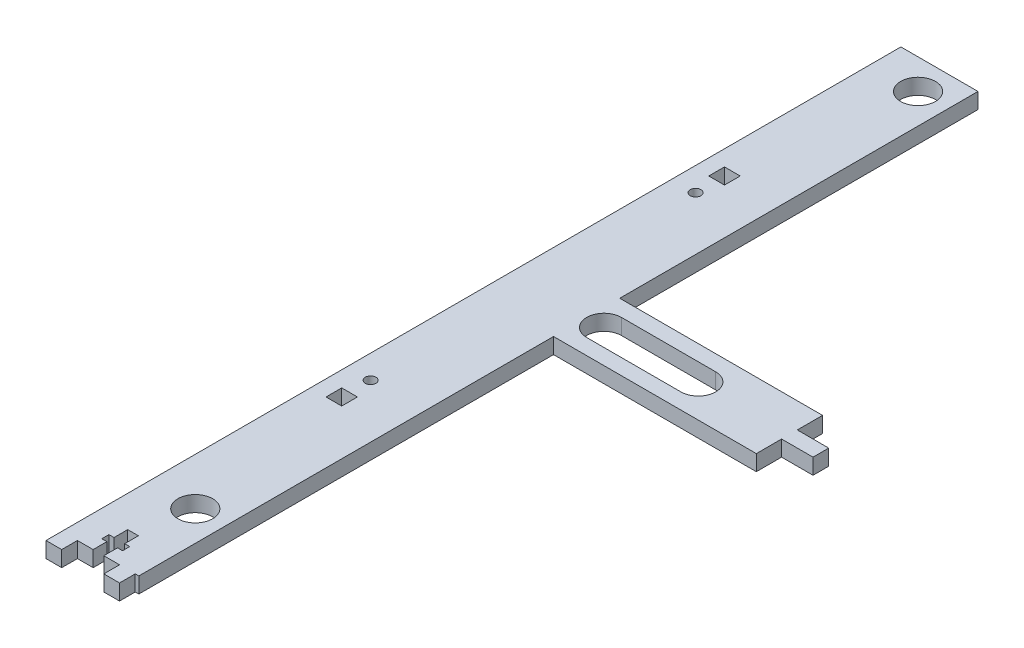
SolidWorks part; units mm, degrees
ref_plane "Front Plane" through (0, 0, 0) normal (0, 0, 1) x (1, 0, 0)
ref_plane "Top Plane" through (0, 0, 0) normal (0, 1, 0) x (1, 0, 0)
ref_plane "Right Plane" through (0, 0, 0) normal (1, 0, 0) x (0, 0, -1)
sketch "Axle Support Plate" plane through (0, 0, 0) normal (0, 1, 0) x (1, 0, 0)
  line L0 (19.05, 146.05) -> (19.05, -146.05) construction
  line L1 (6.35, 158.1601) -> (6.35, -187.325) construction
  line L2 (6.35, -80.518) -> (6.35, -74.168)
  line L3 (6.35, 80.518) -> (12.7, 80.518)
  line L4 (31.1601, -180.975) -> (31.1601, -13.3801)
  line L5 (0, 0) -> (31.1601, 158.1601) construction
  line L6 (0, 0) -> (31.1601, -180.975) construction
  line L8 (0, 158.1601) -> (31.1601, 158.1601)
  line L9 (6.35, -180.975) -> (12.7, -180.975)
  line L10 (6.35, 80.518) -> (6.35, 74.168)
  line L11 (6.35, 74.168) -> (12.7, 74.168)
  line L12 (0, -187.325) -> (0, 158.1601)
  line L13 (12.7, 80.518) -> (12.7, 74.168)
  line L14 (6.35, -80.518) -> (12.7, -80.518)
  line L15 (12.7, -80.518) -> (12.7, -74.168)
  line L16 (6.35, -74.168) -> (12.7, -74.168)
  line L17 (31.1601, 0) -> (0, 0) construction
  line L18 (0, -187.325) -> (6.35, -187.325)
  line L19 (6.35, -187.325) -> (6.35, -180.975)
  line L20 (23.368, -180.975) -> (23.368, -187.325)
  line L21 (23.368, -187.325) -> (29.718, -187.325)
  line L22 (29.718, -187.325) -> (29.718, -180.975)
  line L23 (29.718, -180.975) -> (31.1601, -180.975)
  line L24 (9.525, 80.518) -> (9.525, 65.659) construction
  line L25 (12.7, -180.975) -> (12.7, -175.44)
  line L26 (12.7, -175.44) -> (10.659, -175.44)
  line L27 (10.659, -175.44) -> (10.659, -172.54)
  line L28 (10.659, -172.54) -> (12.7, -172.54)
  line L29 (12.7, -172.54) -> (12.7, -167.005)
  line L30 (12.7, -167.005) -> (17.018, -167.005)
  line L31 (17.018, -167.005) -> (17.018, -172.54)
  line L32 (17.018, -172.54) -> (19.059, -172.54)
  line L33 (19.059, -172.54) -> (19.059, -175.44)
  line L34 (19.059, -175.44) -> (17.018, -175.44)
  line L35 (17.018, -175.44) -> (17.018, -180.975)
  line L36 (17.018, -180.975) -> (23.368, -180.975)
  line L37 (31.1601, 13.3801) -> (113.1203, 13.3801)
  line L38 (113.1203, 13.3801) -> (113.1203, 3.175)
  line L39 (113.1203, -13.3801) -> (31.1601, -13.3801)
  line L40 (38.1903, 0) -> (76.2903, 0) construction
  line L41 (38.1903, 7.0301) -> (76.2903, 7.0301)
  line L42 (38.1903, -7.0301) -> (76.2903, -7.0301)
  line L43 (113.1203, -3.175) -> (125.8203, -3.175)
  line L44 (125.8203, -3.175) -> (125.8203, 3.175)
  line L45 (125.8203, 3.175) -> (113.1203, 3.175)
  line L46 (31.1601, 13.3801) -> (31.1601, 158.1601)
  line L47 (31.1601, 13.3801) -> (31.1601, -13.3801) construction
  line L48 (31.1601, 0) -> (125.8203, 0) construction
  line L51 (113.1203, -3.175) -> (113.1203, -13.3801)
  circle A0 centre (19.05, 146.05) radius 7.0301
  circle A1 centre (19.05, -146.05) radius 7.0301
  circle A2 centre (9.525, 65.659) radius 2.159
  circle A3 centre (9.525, -65.659) radius 2.159
  arc A4 (38.1903, 7.0301) -> (38.1903, -7.0301) centre (38.1903, 0) ccw
  arc A5 (76.2903, -7.0301) -> (76.2903, 7.0301) centre (76.2903, 0) ccw
  point P0 (0, 0)
  point P15 (19.05, 0)
  point P38 (9.525, 67.818)
  point P57 (57.2403, 0)
  dimension "D1" = 5.08
  dimension "D4" = 14.0603
  dimension "D5" = 5.08
  dimension "D8" = 63.5
  dimension "D14" = 14.0603
  dimension "D15" = 4.318
  dimension "D16" = 6.35
  dimension "D22" = 7.0301
  dimension "D25" = 36.83
  dimension "D2" = 292.1
  dimension "D3" = 6.35
  dimension "D6" = 12.7
  dimension "D7" = 6.35
  dimension "D9" = 6.35
  dimension "D10" = 6.35
  dimension "D11" = 6.35
  dimension "D12" = 13.97
  dimension "D13" = 34.925
  dimension "D17" = 4.318
  dimension "D18" = 8.4
  dimension "D19" = 2.9
  dimension "D20" = 6.35
  dimension "D21" = 6.35
  dimension "D23" = 6.35
  dimension "D24" = 38.1
  dimension "D26" = 12.7
  dimension "D27" = 6.35
extrude "Boss-Extrude1" add sketch "Axle Support Plate" along normal blind 6.35
equation "\"Ball Diameter\"= 1.75in"
equation "\"Sheet Thickness\"= 0.25in"
equation "\"Screw Diameter\"= .17in"
equation "\"Robot Diameter\"= 14in"
equation "\"Castor Screw Diameter\"= 0.22in"
equation "\"Wheel Diameter\" = 4in"
equation "\"Nut Diameter\" = 8.4mm"
equation "\"Nut Height\" = 2.9mm"
equation "\"Screw Height\" = 0.55in"
equation "\"Pulley Diameter\" = 1in"
equation "\"Reactor Height\" = 14in"
equation "\"Elevator Height\" = 11.5in"
equation "\"Elevator Width\" = \"Ball Diameter\" + 0.25in"
equation "\"D2@Axle Support Plate\"=\"Elevator Height\""
equation "\"D1@Boss-Extrude1\"=\"Sheet Thickness\""
equation "\"Elevator Bearing Diameter\" = sqr(2*(\"Sheet Thickness\"^2)) + 0.2in"
equation "\"Elevator Axle Length\" = \"Elevator Width\" + 8*\"Sheet Thickness\""
equation "\"D4@Axle Support Plate\"=\"Elevator Bearing Diameter\""
equation "\"D6@Axle Support Plate\"=(\"Pulley Diameter\")/2"
equation "\"D3@Axle Support Plate\"=\"Sheet Thickness\""
equation "\"D7@Axle Support Plate\"=\"Sheet Thickness\""
equation "\"D10@Axle Support Plate\"=\"Sheet Thickness\""
equation "\"D11@Axle Support Plate\"=\"Sheet Thickness\""
equation "\"D12@Axle Support Plate\"=\"Screw Height\""
equation "\"D13@Axle Support Plate\"=2.5in - \"Sheet Thickness\" - (\"Ball Diameter\")/2"
equation "\"D9@Axle Support Plate\"=\"Sheet Thickness\""
equation "\"D14@Axle Support Plate\"=\"Elevator Bearing Diameter\""
equation "\"D15@Axle Support Plate\"=\"Screw Diameter\""
equation "\"D16@Axle Support Plate\"=\"Sheet Thickness\""
equation "\"D17@Axle Support Plate\"=\"Screw Diameter\""
equation "\"D18@Axle Support Plate\"=\"Nut Diameter\""
equation "\"D19@Axle Support Plate\"=\"Nut Height\""
equation "\"D20@Axle Support Plate\"=\"Sheet Thickness\""
equation "\"D21@Axle Support Plate\"=\"Sheet Thickness\""
equation "\"D22@Axle Support Plate\"=\"Elevator Bearing Diameter\"/2"
equation "\"D23@Axle Support Plate\"=\"Sheet Thickness\""
equation "\"Elevator Axle Endcap Diameter\" = \"Pulley Diameter\" + 0.25in"
equation "\"D25@Axle Support Plate\"=\"Elevator Axle Endcap Diameter\"+0.2in"
equation "\"D27@Axle Support Plate\"=\"Sheet Thickness\""
